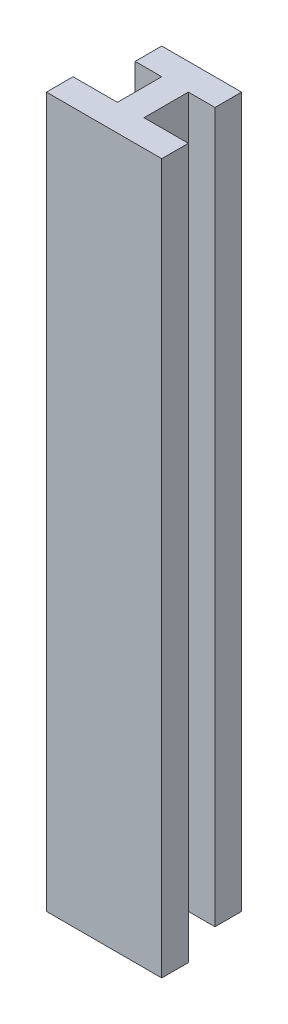
SolidWorks part; units mm, degrees
ref_plane "前视基准面" through (0, 0, 0) normal (0, 0, 1) x (1, 0, 0)
ref_plane "上视基准面" through (0, 0, 0) normal (0, 1, 0) x (1, 0, 0)
ref_plane "右视基准面" through (0, 0, 0) normal (1, 0, 0) x (0, 0, -1)
other "Configuration Table"
sketch "草图1" plane through (0, 0, 0) normal (0, 1, 0) x (1, 0, 0)
  line L0 (0, 0) -> (13, 0)
  line L1 (13, 0) -> (13, 3)
  line L2 (13, 3) -> (8, 3)
  line L3 (8, 3) -> (8, 8)
  line L4 (8, 8) -> (11, 8)
  line L5 (11, 8) -> (11, 11)
  line L6 (11, 11) -> (2, 11)
  line L7 (2, 11) -> (2, 8)
  line L8 (2, 8) -> (5, 8)
  line L9 (0, 0) -> (0, 3)
  line L10 (0, 3) -> (5, 3)
  line L11 (5, 3) -> (5, 8)
  point P3 (0, 0)
  dimension "D1" = 13
  dimension "D2" = 3
  dimension "D3" = 5
  dimension "D4" = 5
  dimension "D5" = 5
  dimension "D6" = 5
  dimension "D7" = 3
  dimension "D8" = 3
  dimension "D9" = 3
extrude "凸台-拉伸1" add sketch "草图1" along normal blind 80
